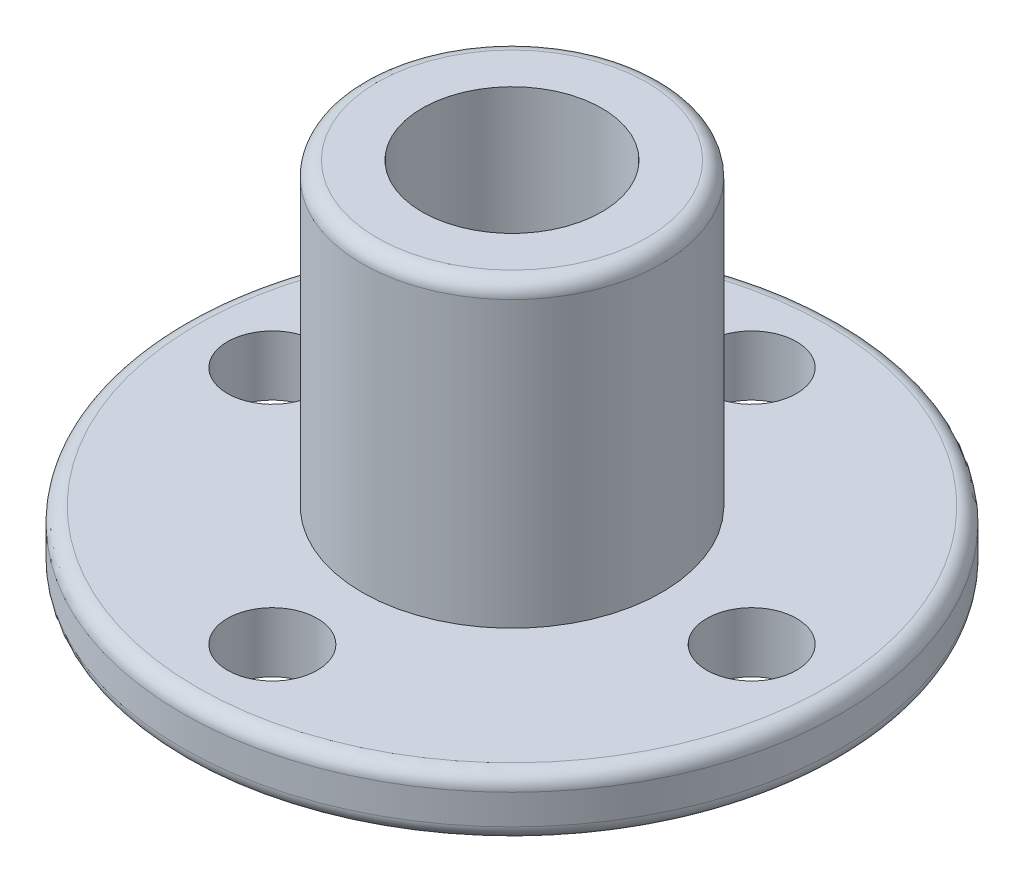
SolidWorks part; units mm, degrees
ref_plane "前视基准面" through (0, 0, 0) normal (0, 0, 1) x (1, 0, 0)
ref_plane "上视基准面" through (0, 0, 0) normal (0, 1, 0) x (1, 0, 0)
ref_plane "右视基准面" through (0, 0, 0) normal (1, 0, 0) x (0, 0, -1)
other "Configuration Table"
sketch "草图1" plane through (0, 0, 0) normal (0, 1, 0) x (1, 0, 0)
  line L0 (0, 0) -> (20.468, 0) construction
  line L1 (0, 0) -> (0, 13.8298) construction
  circle A0 centre (0, 0) radius 11
  dimension "D1" = 22
extrude "凸台-拉伸1" add sketch "草图1" along normal blind 2
sketch "草图2" plane through (0, 2, 0) normal (0, 1, 0) x (1, 0, 0)
  line L0 (0, 0) -> (17.1618, 0) construction
  line L1 (0, 0) -> (0, 8.7626) construction
  line L2 (-11, 0) -> (-11, 1.8053) construction
  line L3 (0, 11) -> (1.8198, 11) construction
  circle A3 centre (0, 8) radius 1.5
  circle A4 centre (8, 0) radius 1.5
  circle A5 centre (0, -8) radius 1.5
  circle A6 centre (-8, 0) radius 1.5
  circle A7 centre (0, 0) radius 11 construction
  dimension "D1" = 3
  dimension "D4" = 3
  dimension "D5" = 3
  dimension "D6" = 3
  dimension "D2" = 16
  dimension "D3" = 16
  dimension "D7" = 3
  dimension "D8" = 3
extrude "切除-拉伸1" cut sketch "草图2" against normal blind 2
sketch "草图3" plane through (0, 2, 0) normal (0, 1, 0) x (1, 0, 0)
  circle A0 centre (0, 0) radius 5
extrude "凸台-拉伸2" add sketch "草图3" along normal blind 10
sketch "草图4" plane through (0, 12, 0) normal (0, 1, 0) x (1, 0, 0)
  circle A0 centre (0, 0) radius 3
  dimension "D1" = 6
extrude "切除-拉伸2" cut sketch "草图4" against normal blind 12
fillet "圆角1" radius 0.5 3 edges at (0, 12, 5) (0, 0, 11) (0, 2, 11)
sketch "草图5" plane through (0, 0, 0) normal (0, 0, 1) x (1, 0, 0)
  line L0 (3, 12) -> (-3, 12) construction
  circle A0 centre (0, 7) radius 1.5
  dimension "D1" = 3
  dimension "D2" = 5
extrude "切除-拉伸3" cut sketch "草图5" against normal up to next contours A0
